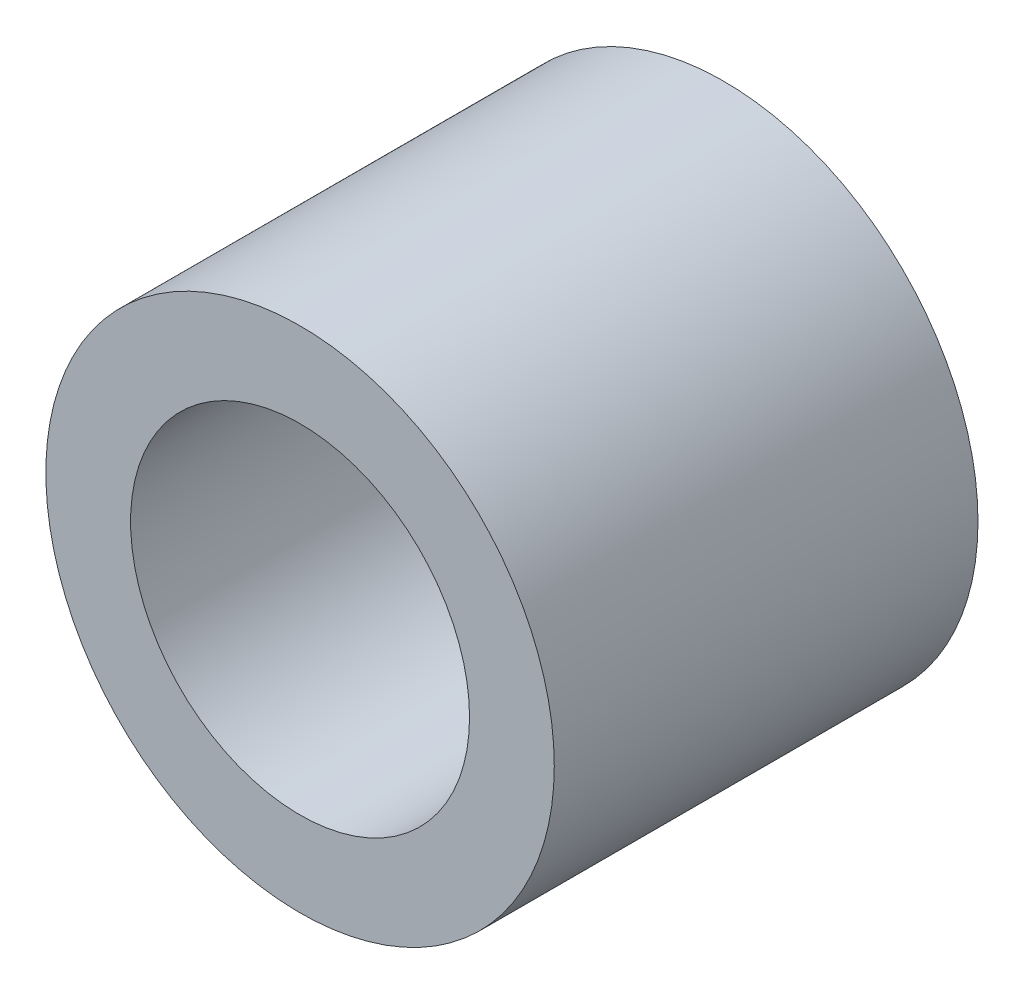
SolidWorks part; units mm, degrees
ref_plane "Front Plane" through (0, 0, 0) normal (0, 0, 1) x (1, 0, 0)
ref_plane "Top Plane" through (0, 0, 0) normal (0, 1, 0) x (1, 0, 0)
ref_plane "Right Plane" through (0, 0, 0) normal (1, 0, 0) x (0, 0, -1)
sketch "Sketch1" plane through (0, 0, 0) normal (0, 0, 1) x (1, 0, 0)
  circle A0 centre (0, 0) radius 152.4
  circle A1 centre (0, 0) radius 101.6
  dimension "D1" = 304.8
  dimension "D2" = 203.2
extrude "Boss-Extrude1" add sketch "Sketch1" along normal mid plane 254
